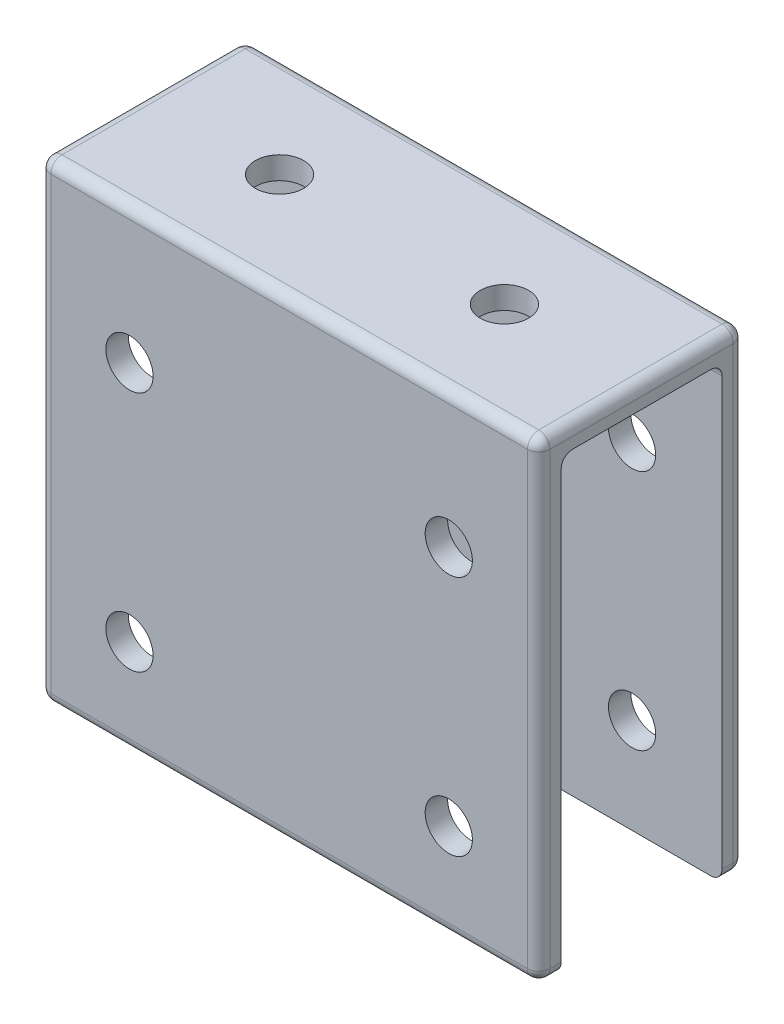
SolidWorks part; units mm, degrees
ref_plane "Front Plane" through (0, 0, 0) normal (0, 0, 1) x (1, 0, 0)
ref_plane "Top Plane" through (0, 0, 0) normal (0, 1, 0) x (1, 0, 0)
ref_plane "Right Plane" through (0, 0, 0) normal (1, 0, 0) x (0, 0, -1)
sketch "Sketch1" plane through (0, 0, 0) normal (0, 0, 1) x (1, 0, 0)
  line L0 (22.2, 40) -> (22.2, 0) construction
  line L1 (0, 0) -> (44.4, 0)
  line L2 (0, 0) -> (0, 40)
  line L3 (0, 40) -> (44.4, 40)
  line L4 (44.4, 0) -> (44.4, 40)
  line L5 (0, 0) -> (8, 0) construction
  line L6 (0, 0) -> (0, 8) construction
  line L10 (8, 29.9769) -> (8, 27.8769) construction
  line L11 (8, 19) -> (8, 8.4769) construction
  line L12 (8, 19) -> (10.573, 19) construction
  line L15 (10.573, 19) -> (10.573, 40) construction
  line L16 (8, 8.4769) -> (36.4, 8.4769) construction
  line L17 (36.4, 8.4769) -> (36.4, 29.9769) construction
  circle A0 centre (8, 8.4769) radius 2.1
  circle A1 centre (8, 29.9769) radius 2.1
  circle A2 centre (36.4, 29.9769) radius 2.1
  circle A3 centre (36.4, 8.4769) radius 2.1
  dimension "D5" = 4.2
  dimension "D6" = 4.2
  dimension "D7" = 4.2
  dimension "D8" = 4.2
  dimension "D1" = 44.4
  dimension "D2" = 40
  dimension "D3" = 21.5
  dimension "D4" = 21.5
  dimension "D9" = 21
  dimension "D10" = 8
  dimension "D11" = 8
extrude "Boss-Extrude1" add sketch "Sketch1" along normal blind 2
sketch "Sketch2" plane through (0, 40, 0) normal (0, 1, 0) x (1, 0, 0)
  line L0 (44.4, -2) -> (44.4, 0) construction
  line L1 (0, -2) -> (44.4, -2)
  line L2 (0, -2) -> (0, 16.3)
  line L3 (0, 16.3) -> (44.4, 16.3)
  line L4 (44.4, -2) -> (44.4, 16.3)
  dimension "D1" = 18.3
  dimension "D2" = 44.4
extrude "Boss-Extrude2" add sketch "Sketch2" along normal blind 2
pattern_linear "LPattern1" count 2 spacing 16.3 along (0, 0, -1) of "Boss-Extrude1"
sketch "Sketch3" plane through (0, 42, 0) normal (0, 1, 0) x (1, 0, 0)
  line L0 (22.2, 16.3) -> (22.2, -2) construction
  line L1 (44.4, 16.3) -> (0, 16.3) construction
  line L2 (0, -2) -> (44.4, -2) construction
  line L3 (22.2, 7.15) -> (12.2, 7.15) construction
  line L4 (22.2, 7.15) -> (32.2, 7.15) construction
  circle A0 centre (12.2, 7.15) radius 2.15
  circle A1 centre (32.2, 7.15) radius 2.15
  dimension "D3" = 4.3
  dimension "D4" = 4.3
  dimension "D1" = 10
  dimension "D2" = 10
extrude "Cut-Extrude1" cut sketch "Sketch3" against normal through all
fillet "Fillet4" radius 1 16 edges at (22.2, 40, -14.3) (22.2, 40, 0) (22.2, 42, -16.3) (0, 42, -7.15) (22.2, 42, 2) (44.4, 42, -7.15) (44.4, 21, 2) (44.4, 21, -16.3) (0, 21, -16.3) (0, 21, 2) (44.4, 0, 1) (0, 0, 1) (44.4, 0, -15.3) (0, 0, -15.3) (22.2, 0, -16.3) (22.2, 0, 2)
